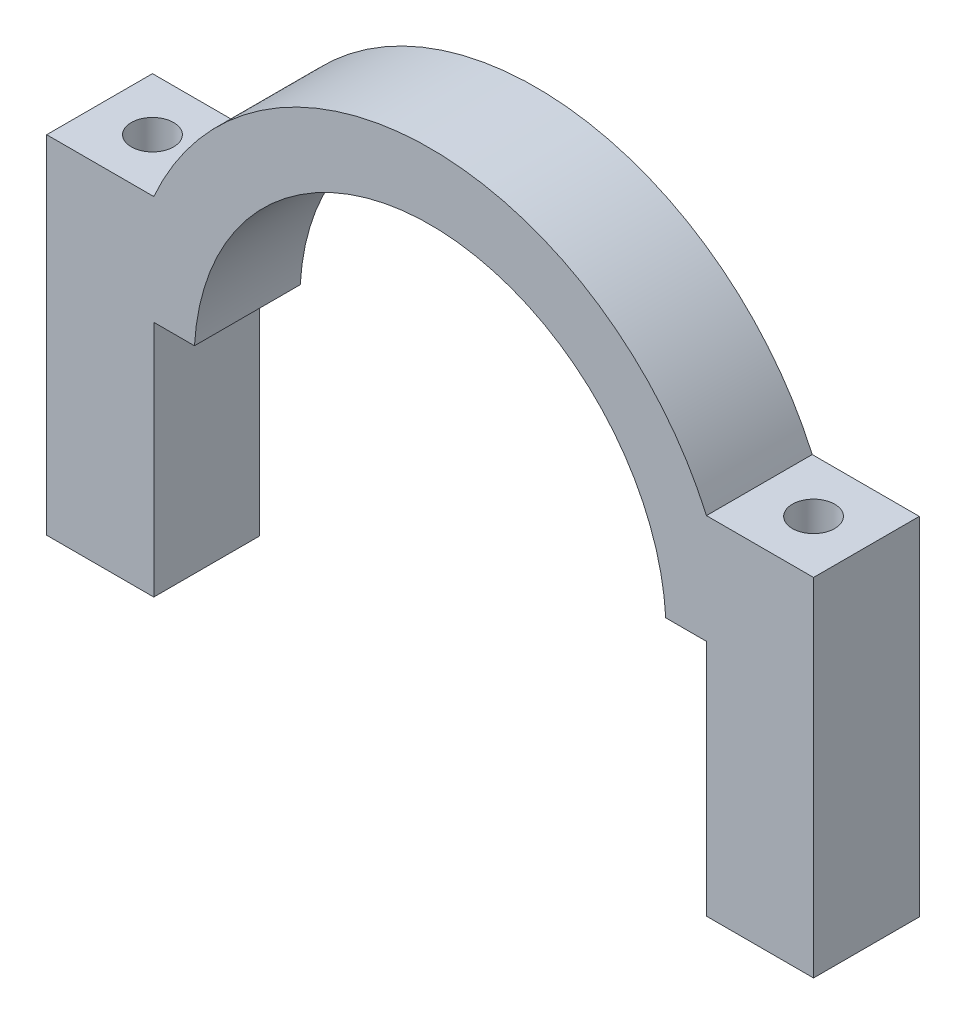
SolidWorks part; units mm, degrees
material "5052-O"
ref_plane "正面" through (0, 0, 0) normal (0, 0, 1) x (1, 0, 0)
ref_plane "平面" through (0, 0, 0) normal (0, 1, 0) x (1, 0, 0)
ref_plane "右側面" through (0, 0, 0) normal (1, 0, 0) x (0, 0, -1)
sketch "ｽｹｯﾁ1" plane through (0, 0, 0) normal (0, 0, 1) x (1, 0, 0)
  line L0 (-10.458, 0) -> (0, 0) construction
  line L1 (-20.9, 9.2365) -> (-29, 9.2365)
  line L2 (-29, 9.2365) -> (-29, -17)
  line L3 (-29, -17) -> (-20.9, -17)
  line L4 (-20.9, -17) -> (-20.9, 1)
  line L5 (-20.9, 1) -> (-17.822, 1)
  line L6 (17.822, 1) -> (20.9, 1)
  line L7 (20.9, 1) -> (20.9, -17)
  line L8 (20.9, -17) -> (29, -17)
  line L9 (29, -17) -> (29, 9.2365)
  line L10 (29, 9.2365) -> (20.9, 9.2365)
  arc A0 (20.9, 9.2365) -> (-20.9, 9.2365) centre (0, 0) ccw
  arc A1 (-17.822, 1) -> (17.822, 1) centre (0, 0) cw
  arc A2 (-17.822, 1) -> (17.822, 1) centre (0, 0) ccw construction
  point P16 (-17.85, 0)
  dimension "D3" = 17.85
  dimension "D4" = 5
  dimension "D1" = 1
  dimension "D2" = 3.05
  dimension "D5" = 8.1
  dimension "D6" = 17
extrude "ﾎﾞｽ - 押し出し1" add sketch "ｽｹｯﾁ1" along normal blind 8
sketch "ｽｹｯﾁ2" plane through (0, -17, 0) normal (0, -1, 0) x (1, 0, 0)
  line L0 (-29, 4) -> (29, 4) construction
  line L1 (-29, 8) -> (-29, 0) construction
  line L2 (29, 8) -> (29, 0) construction
  line L4 (0, 0) -> (0, 8) construction
  line L5 (17.822, 8) -> (-17.822, 8) construction
  circle A0 centre (-25, 4) radius 1.6
  circle A1 centre (25, 4) radius 1.6
  dimension "D2" = 3.2
  dimension "D1" = 4
extrude "ｶｯﾄ - 押し出し1" cut sketch "ｽｹｯﾁ2" against normal through all and the other way through all
